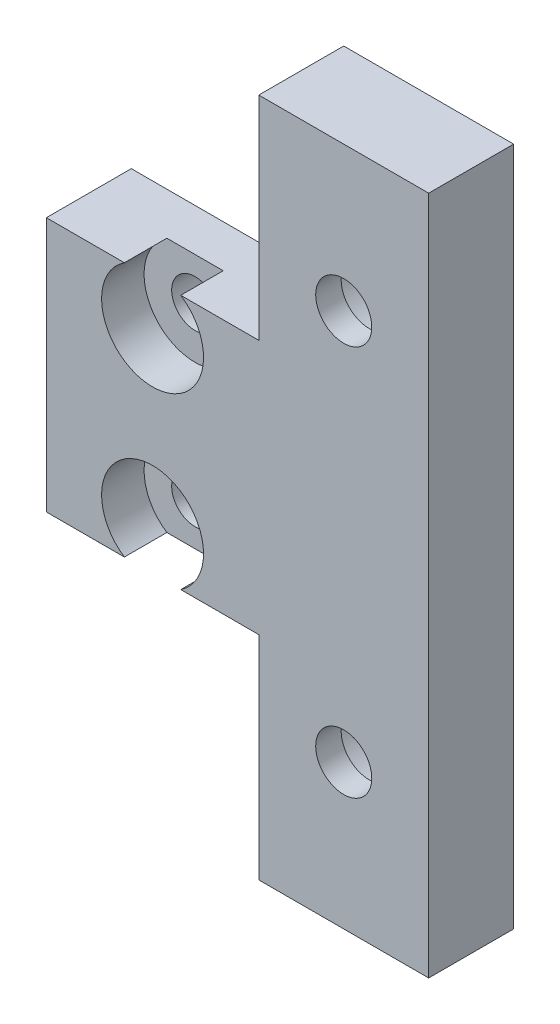
SolidWorks part; units mm, degrees
ref_plane "Plan de face" through (0, 0, 0) normal (0, 0, 1) x (1, 0, 0)
ref_plane "Plan de dessus" through (0, 0, 0) normal (0, 1, 0) x (1, 0, 0)
ref_plane "Plan de droite" through (0, 0, 0) normal (1, 0, 0) x (0, 0, -1)
sketch "Esquisse1" plane through (0, 0, 0) normal (0, 0, 1) x (1, 0, 0)
  line L0 (-1.1643, 10.8998) -> (-1.1643, -35.1002) construction
  line L4 (8.8357, 27.8998) -> (8.8357, -52.1002)
  line L5 (8.8357, 27.8998) -> (-11.1643, 27.8998)
  line L6 (-11.1643, 27.8998) -> (-11.1643, 2.8998)
  line L7 (-11.1643, 2.8998) -> (-36.1643, 2.8998)
  line L8 (-36.1643, 2.8998) -> (-36.1643, -27.1002)
  line L9 (-36.1643, -27.1002) -> (-11.1643, -27.1002)
  line L10 (-11.1643, -27.1002) -> (-11.1643, -52.1002)
  line L11 (-11.1643, -52.1002) -> (8.8357, -52.1002)
  line L12 (-23.6643, -2.1002) -> (-23.6643, -22.1002) construction
  circle A0 centre (-1.1643, 10.8998) radius 3.3
  circle A3 centre (-1.1643, -35.1002) radius 3.3
  circle A4 centre (-23.6643, -2.1002) radius 2.75
  circle A7 centre (-23.6643, -22.1002) radius 2.75
  point P9 (-1.1643, 27.8998)
  point P12 (-1.1643, -12.1002)
  point P13 (8.8357, -12.1002)
  point P17 (-23.6643, -12.1002)
  point P18 (-23.6643, 2.8998)
  point P19 (-36.1643, -12.1002)
  dimension "D1" = 6.6
  dimension "D7" = 5.5
  dimension "D3" = 6.6
  dimension "D2" = 25
  dimension "D4" = 46
  dimension "D5" = 80
  dimension "D6" = 30
  dimension "D8" = 20
  dimension "D9" = 20
extrude "Boss.-Extru.1" add sketch "Esquisse1" along normal blind 10
sketch "Esquisse2" plane through (0, 0, 10) normal (0, 0, 1) x (1, 0, 0)
  circle A4 centre (-23.6643, -2.1002) radius 6
  circle A5 centre (-23.6643, -22.1002) radius 6
  dimension "D1" = 12
extrude "Enlèv. mat.-Extru.1" cut sketch "Esquisse2" against normal blind 5
sketch "Esquisse3" plane through (0, 0, 0) normal (0, 0, -1) x (-1, 0, 0)
  circle A8 centre (1.1643, 10.8998) radius 7
  circle A9 centre (1.1643, -35.1002) radius 7
  dimension "D1" = 14
extrude "Enlèv. mat.-Extru.3" cut sketch "Esquisse3" against normal blind 7
